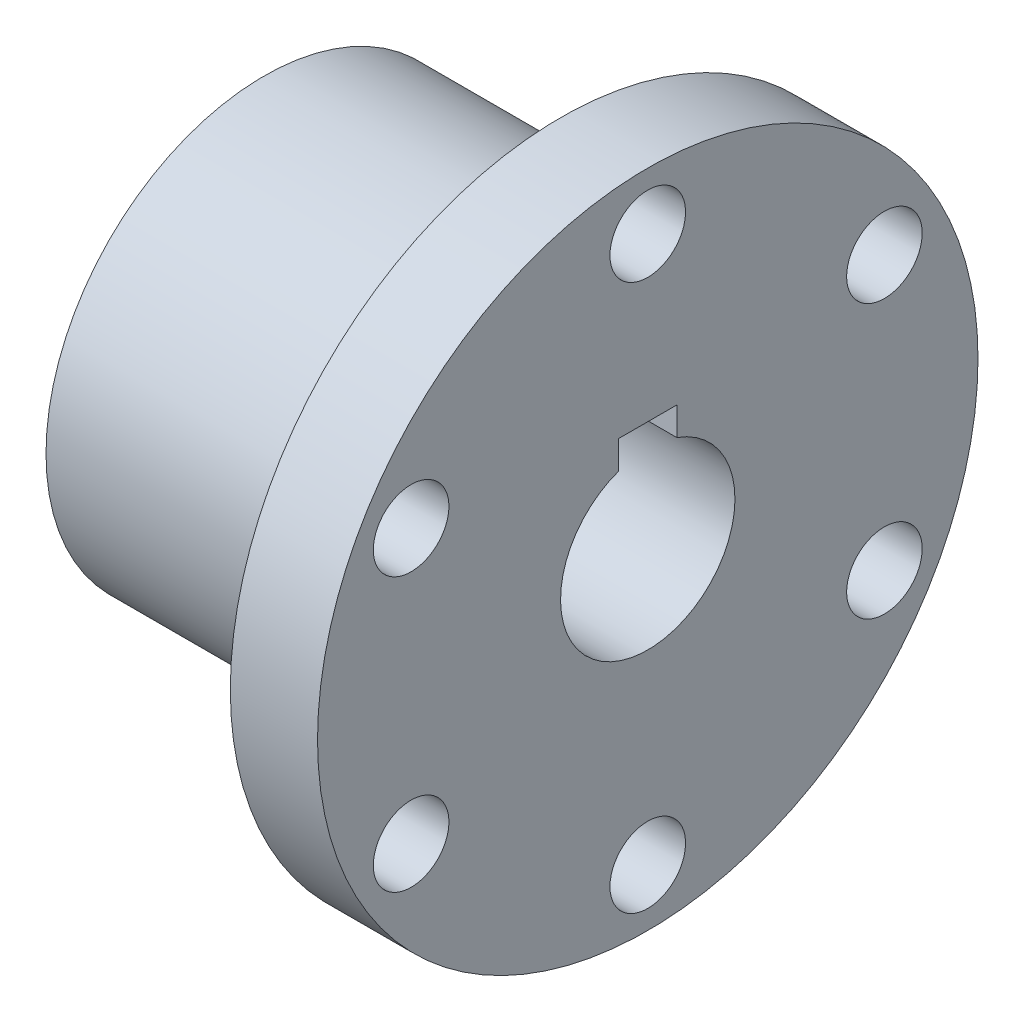
SolidWorks part; units mm, degrees
ref_plane "前视基准面" through (0, 0, 0) normal (0, 0, 1) x (1, 0, 0)
ref_plane "上视基准面" through (0, 0, 0) normal (0, 1, 0) x (1, 0, 0)
ref_plane "右视基准面" through (0, 0, 0) normal (1, 0, 0) x (0, 0, -1)
sketch "草图1" plane through (0, 0, 0) normal (0, 0, 1) x (1, 0, 0)
  line L0 (0, 6) -> (0, 15)
  line L1 (0, 15) -> (20.4, 15)
  line L2 (20.4, 15) -> (20.4, 22.72)
  line L3 (20.4, 22.72) -> (26.4, 22.72)
  line L4 (26.4, 22.72) -> (26.4, 6)
  line L5 (26.4, 6) -> (0, 6)
  line L6 (0, 0) -> (54.1123, 0) construction
  dimension "D1" = 45.44
  dimension "D2" = 12
  dimension "D3" = 26.4
  dimension "D4" = 6
  dimension "D5" = 30
revolve "旋转1" add sketch "草图1" angle 360 about L6
hole_wizard "Ø5.2 (5.2) 直径孔1" positions "草图2" profile "草图3" hole size "Ø5.2" standard "GB" end condition through all
sketch "草图2" plane through (20.4, 0, 0) normal (-1, 0, 0) x (0, 0, 1)
  point P0 (0, 18.8)
  point P6 (16.2813, -9.4)
  point P7 (-16.2813, -9.4)
  point P10 (0, -18.8)
  point P16 (-16.2813, 9.4)
  point P17 (16.2813, 9.4)
  dimension "D2" = 18.8
  dimension "D4" = 18.8
  dimension "D1" = 3
  dimension "D3" = 3
sketch "草图3" plane through (20.4, 18.8, 0) normal (0, 1, 0) x (0, 0, 1)
  line L0 (0, 0) -> (0, 6)
  line L1 (0, 6) -> (2.6, 6)
  line L2 (2.6, 6) -> (2.6, 0.025)
  line L3 (2.6, 0.025) -> (2.625, 0)
  line L5 (2.625, 0) -> (0, 0)
  line L6 (-2.6, 0.025) -> (-2.625, 0) construction
  line L11 (0, -6.35) -> (0, 107.95) construction
  dimension "通孔孔直径" = 5.2
  dimension "通孔孔深度" = 6
  dimension "近端锥形沉头孔直径" = 5.25
  dimension "近端锥形沉头孔角度" = 90
sketch "草图4" plane through (0, 0, 0) normal (-1, 0, 0) x (0, 0, 1)
  line L1 (-2, 2.8639) -> (2, 2.8639)
  line L2 (-2, 2.8639) -> (-2, 7.6)
  line L3 (-2, 7.6) -> (2, 7.6)
  line L4 (2, 2.8639) -> (2, 7.6)
  circle A0 centre (0, 0) radius 6 construction
  point P4 (0, 2.8639)
  point P6 (0, 6)
  dimension "D1" = 1.6
  dimension "D2" = 4
extrude "切除-拉伸1" cut sketch "草图4" against normal blind 35
